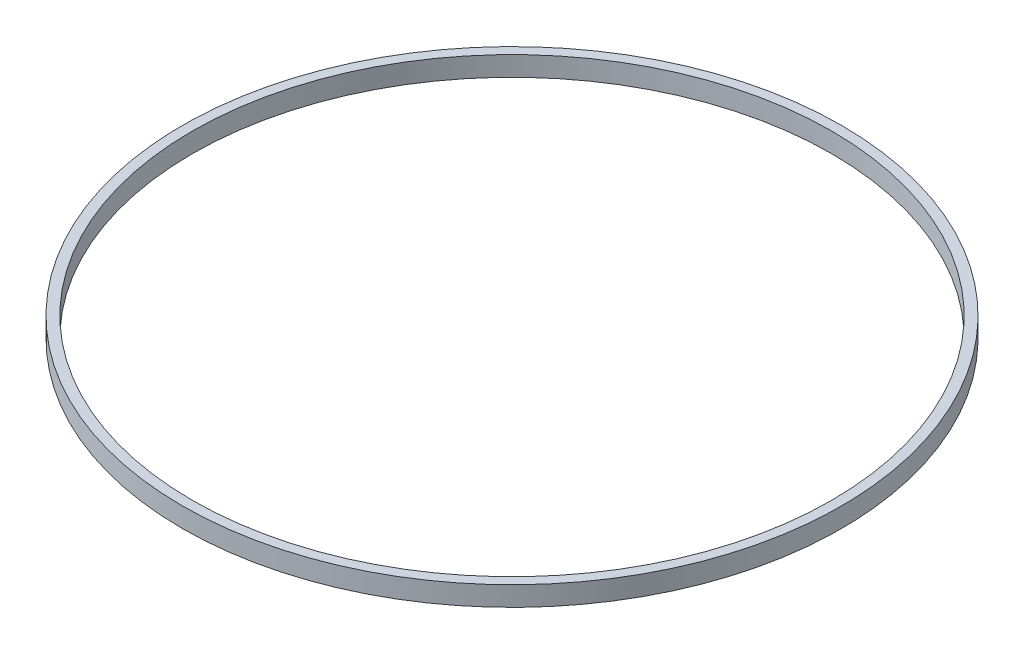
SolidWorks part; units mm, degrees
material "Custom Plastic"
ref_plane "Front Plane" through (0, 0, 0) normal (0, 0, 1) x (1, 0, 0)
ref_plane "Top Plane" through (0, 0, 0) normal (0, 1, 0) x (1, 0, 0)
ref_plane "Right Plane" through (0, 0, 0) normal (1, 0, 0) x (0, 0, -1)
sketch "Sketch1" plane through (0, 0, 0) normal (0, 1, 0) x (1, 0, 0)
  circle A0 centre (0, 0) radius 67.1
  circle A1 centre (0, 0) radius 65.1
  dimension "D1" = 2
  dimension "D2" = 134.2
extrude "Boss-Extrude2" add sketch "Sketch1" along normal blind 4
